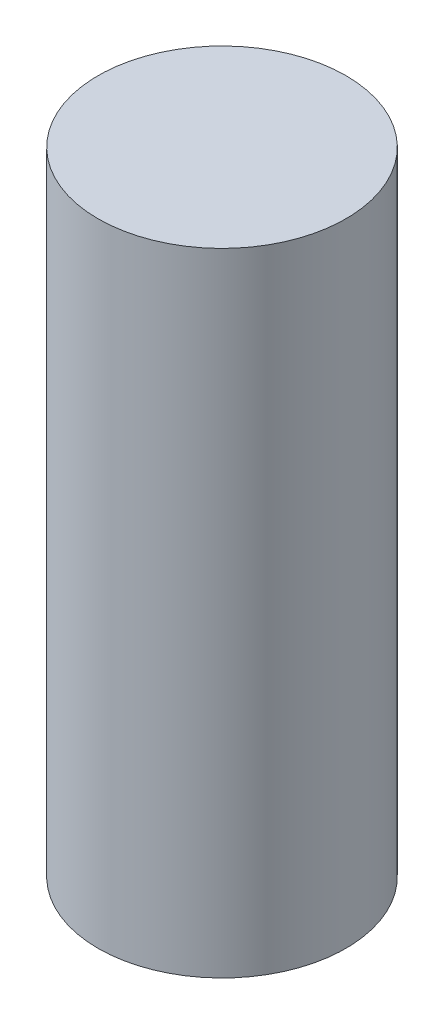
SolidWorks part; units mm, degrees
ref_plane "Alzado" through (0, 0, 0) normal (0, 0, 1) x (1, 0, 0)
ref_plane "Planta" through (0, 0, 0) normal (0, 1, 0) x (1, 0, 0)
ref_plane "Vista lateral" through (0, 0, 0) normal (1, 0, 0) x (0, 0, -1)
sketch "Croquis1" plane through (0, 0, 0) normal (0, 1, 0) x (1, 0, 0)
  circle A0 centre (0, 0) radius 64.75
extrude "Saliente-Extruir1" add sketch "Croquis1" along normal blind 330
